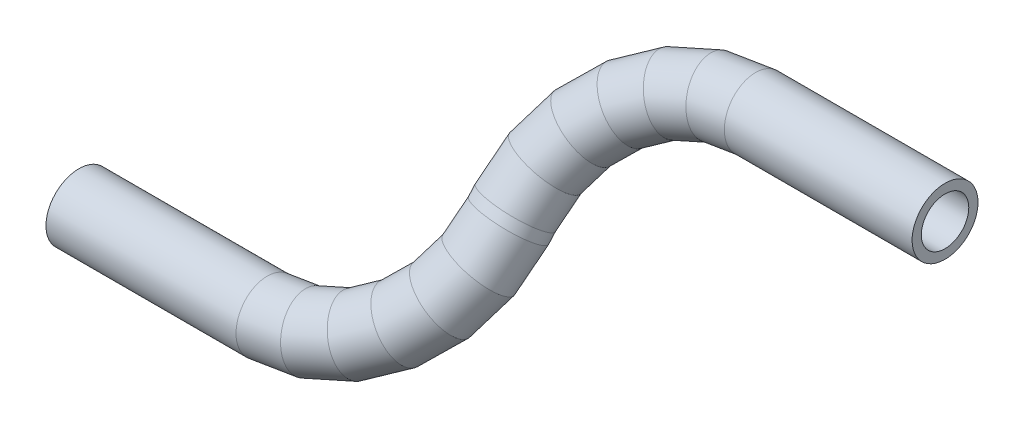
SolidWorks part; units mm, degrees
ref_plane "Front Plane" through (0, 0, 0) normal (0, 0, 1) x (1, 0, 0)
ref_plane "Top Plane" through (0, 0, 0) normal (0, 1, 0) x (1, 0, 0)
ref_plane "Right Plane" through (0, 0, 0) normal (1, 0, 0) x (0, 0, -1)
sketch3d "Path"
  line L0 (-2080.988, -26.6976, 19.3969) -> (-2099.188, -26.6976, 19.3969)
  line L1 (-2099.188, -26.6976, 19.3969) -> (-2102.9091, -27.0769, 19.6725)
  line L2 (-2102.9091, -27.0769, 19.6725) -> (-2106.3976, -28.1912, 20.4821)
  line L3 (-2106.3976, -28.1912, 20.4821) -> (-2109.4353, -29.9708, 21.7751)
  line L4 (-2109.4353, -29.9708, 21.7751) -> (-2111.8324, -32.3044, 23.4705)
  line L5 (-2111.8324, -32.3044, 23.4705) -> (-2113.439, -35.0462, 25.4625)
  line L6 (-2113.439, -35.0462, 25.4625) -> (-2114.1547, -38.0247, 27.6266)
  line L7 (-2114.1547, -38.0247, 27.6266) -> (-2114.2213, -38.8319, 28.213)
  line L8 (-2114.2213, -38.8319, 28.213) -> (-2114.9369, -41.8104, 30.3771)
  line L9 (-2114.9369, -41.8104, 30.3771) -> (-2116.5435, -44.5522, 32.3691)
  line L10 (-2116.5435, -44.5522, 32.3691) -> (-2118.9406, -46.8858, 34.0645)
  line L11 (-2118.9406, -46.8858, 34.0645) -> (-2121.9784, -48.6654, 35.3575)
  line L12 (-2121.9784, -48.6654, 35.3575) -> (-2125.4668, -49.7797, 36.1671)
  line L13 (-2125.4668, -49.7797, 36.1671) -> (-2129.188, -50.1591, 36.4427)
  line L14 (-2129.188, -50.1591, 36.4427) -> (-2147.388, -50.1591, 36.4427)
ref_plane "Start Plane" through (-2080.988, 0, 0) normal (1, 0, 0) x (0, 0, -1)
sketch "Profile" plane through (-2080.988, 0, 0) normal (1, 0, 0) x (0, 0, -1)
  circle A0 centre (-19.3969, -26.6976) radius 3.175
  circle A1 centre (-19.3969, -26.6976) radius 2.286
sweep "Tube" add profiles "Profile" path "Path"
